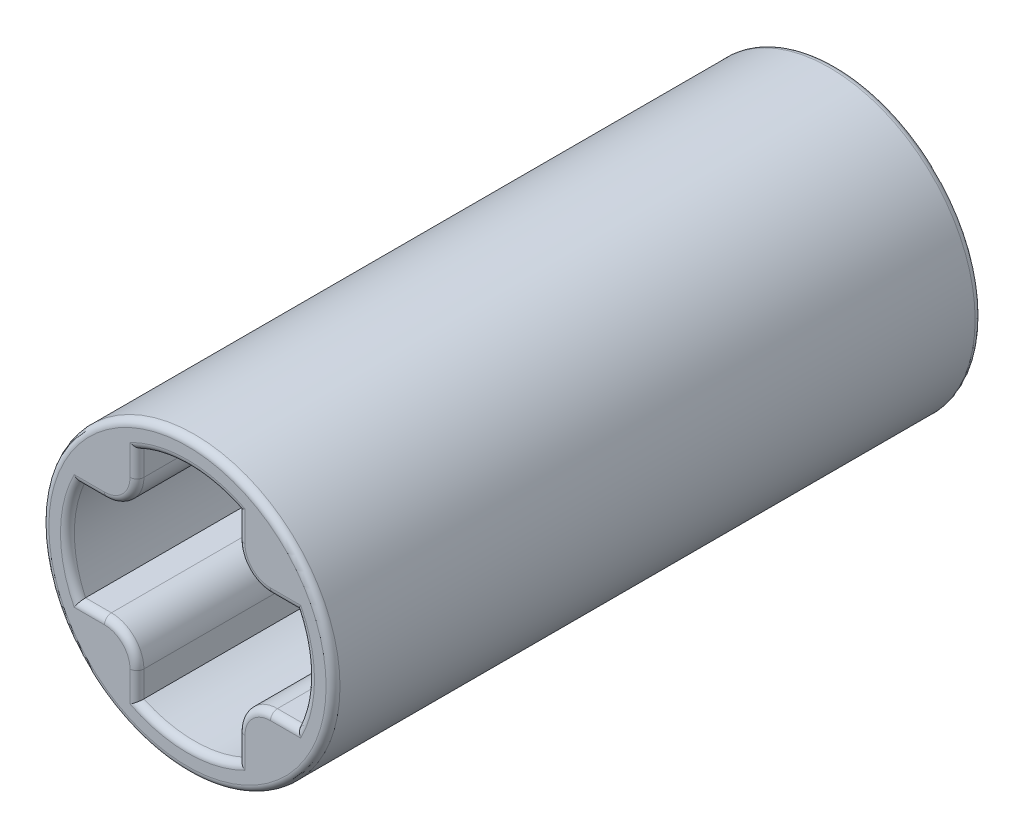
SolidWorks part; units mm, degrees
ref_plane "Front Plane" through (0, 0, 0) normal (0, 0, 1) x (1, 0, 0)
ref_plane "Top Plane" through (0, 0, 0) normal (0, 1, 0) x (1, 0, 0)
ref_plane "Right Plane" through (0, 0, 0) normal (1, 0, 0) x (0, 0, -1)
sketch "Sketch1" plane through (0, 0, 0) normal (0, 0, 1) x (1, 0, 0)
  circle A0 centre (0, 0) radius 1.1
  circle A1 centre (0, 0) radius 3.14
  dimension "D1" = 2.2
  dimension "D2" = 6.28
extrude "Boss-Extrude1" add sketch "Sketch1" along normal blind 6
sketch "Sketch2" plane through (0, 0, 6) normal (0, 0, 1) x (1, 0, 0)
  line L0 (0.89, 0.89) -> (0.89, 2.2181) construction
  line L1 (0.89, 0.89) -> (2.2181, 0.89) construction
  line L2 (2.2181, -0.89) -> (0.89, -0.89) construction
  line L3 (0.89, -0.89) -> (0.89, -2.2181) construction
  line L4 (-0.89, -2.2181) -> (-0.89, -0.89) construction
  line L5 (-0.89, -0.89) -> (-2.2181, -0.89) construction
  line L6 (-2.2181, 0.89) -> (-0.89, 0.89) construction
  line L7 (-0.89, 0.89) -> (-0.89, 2.2181) construction
  line L8 (1.09, 1.09) -> (2.3495, 1.09)
  line L9 (1.09, 1.09) -> (1.09, 2.3495)
  line L10 (-1.09, 1.09) -> (-1.09, 2.3495)
  line L11 (-2.3495, 1.09) -> (-1.09, 1.09)
  line L12 (-1.09, -1.09) -> (-2.3495, -1.09)
  line L13 (-1.09, -2.3495) -> (-1.09, -1.09)
  line L14 (1.09, -1.09) -> (1.09, -2.3495)
  line L15 (2.3495, -1.09) -> (1.09, -1.09)
  circle A0 centre (0, 0) radius 3.14
  circle A1 centre (0, 0) radius 3.14
  circle A2 centre (0, 0) radius 3.14
  arc A3 (-0.89, 2.2181) -> (0.89, 2.2181) centre (0, 0) cw construction
  arc A4 (-2.2181, 0.89) -> (-2.2181, -0.89) centre (0, 0) ccw construction
  arc A5 (-0.89, -2.2181) -> (0.89, -2.2181) centre (0, 0) ccw construction
  arc A6 (2.2181, -0.89) -> (2.2181, 0.89) centre (0, 0) ccw construction
  arc A7 (2.3495, -1.09) -> (2.3495, 1.09) centre (0, 0) ccw
  arc A8 (-1.09, 2.3495) -> (1.09, 2.3495) centre (0, 0) cw
  arc A9 (-2.3495, 1.09) -> (-2.3495, -1.09) centre (0, 0) ccw
  arc A10 (-1.09, -2.3495) -> (1.09, -2.3495) centre (0, 0) ccw
  line B0 (-0.89, 2.2181) -> (-0.89, 0.89) construction
  line B1 (-0.89, 0.89) -> (-2.2181, 0.89) construction
  line B2 (0.89, 2.2181) -> (0.89, 0.89) construction
  line B3 (0.89, 0.89) -> (2.2181, 0.89) construction
  line B4 (-2.2181, -0.89) -> (-0.89, -0.89) construction
  line B5 (-0.89, -0.89) -> (-0.89, -2.2181) construction
  line B6 (0.89, -2.2181) -> (0.89, -0.89) construction
  line B7 (0.89, -0.89) -> (2.2181, -0.89) construction
  arc B8 (-0.89, 2.2181) -> (0.89, 2.2181) centre (0, 0) cw construction
  arc B9 (-2.2181, 0.89) -> (-2.2181, -0.89) centre (0, 0) ccw construction
  arc B10 (2.2181, 0.89) -> (2.2181, -0.89) centre (0, 0) cw construction
  arc B11 (-0.89, -2.2181) -> (0.89, -2.2181) centre (0, 0) ccw construction
  circle M23 centre (0, 0) radius 3.14
  dimension "D2" = 0.75
  dimension "D1" = 0
  dimension "D3" = 0.2
sketch_block_instance "Lego Axle - Unfilleted-1"
sketch_block "Lego Axle - Unfilleted"
extrude "Boss-Extrude3" add sketch "Sketch2" along normal blind 8 contours A0 A10 L13 L12 A9 L11 L10 A8 L9 L8 A7 L15 L14 M23 | L11 L10 M23 | L9 L8 M23 | L15 L14 M23 | L13 L12 M23
fillet "Fillet2" radius 0.7 4 edges at (-1.09, 1.09, 10) (1.09, 1.09, 10) (1.09, -1.09, 10) (-1.09, -1.09, 10)
fillet "Fillet3" radius 0.15 2 edges at (3.14, 0, 0) (1.1, 0, 0)
fillet "Fillet4" radius 0.15 17 edges at (-1.09, -2.0697, 14) (-1.295, -1.295, 14) (-2.0697, 1.09, 14) (-1.295, 1.295, 14) (1.09, -2.0697, 14) (1.295, -1.295, 14) (2.0697, 1.09, 14) (1.295, 1.295, 14) (0, -2.59, 14) (-2.0697, -1.09, 14) (-2.59, 0, 14) (-1.09, 2.0697, 14) (0, 2.59, 14) (2.59, 0, 14) (2.0697, -1.09, 14) (1.09, 2.0697, 14) (3.14, 0, 14)
